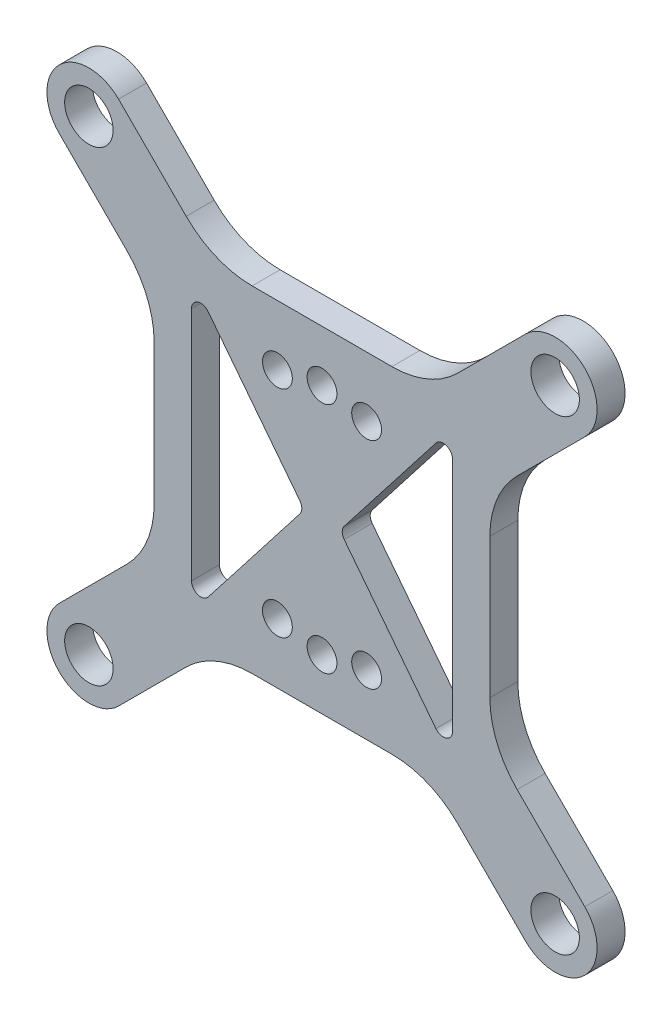
SolidWorks part; units mm, degrees
material "环氧板"
ref_plane "前视基准面" through (0, 0, 0) normal (0, 0, 1) x (1, 0, 0)
ref_plane "上视基准面" through (0, 0, 0) normal (0, 1, 0) x (1, 0, 0)
ref_plane "右视基准面" through (0, 0, 0) normal (1, 0, 0) x (0, 0, -1)
sketch "草图1" plane through (0, 0, 0) normal (0, 0, 1) x (1, 0, 0)
  line L0 (-25, -25) -> (25, 25) construction
  line L1 (-28.182, -21.818) -> (21.818, 28.182)
  line L2 (-21.818, -28.182) -> (28.182, 21.818)
  line L3 (-25, 25) -> (25, -25) construction
  line L4 (-21.818, 28.182) -> (28.182, -21.818)
  line L5 (-28.182, 21.818) -> (21.818, -28.182)
  line L6 (0, 0) -> (122.9733, 0) construction
  line L7 (-25, 25) -> (-25, -25) construction
  line L8 (-25, -25) -> (25, -25) construction
  line L9 (25, -25) -> (25, 25) construction
  line L10 (25, 25) -> (-25, 25) construction
  arc A0 (-28.182, -21.818) -> (-21.818, -28.182) centre (-25, -25) ccw
  arc A1 (28.182, 21.818) -> (21.818, 28.182) centre (25, 25) ccw
  arc A2 (-21.818, 28.182) -> (-28.182, 21.818) centre (-25, 25) ccw
  arc A3 (21.818, -28.182) -> (28.182, -21.818) centre (25, -25) ccw
  circle A4 centre (-25, -25) radius 2.6
  circle A5 centre (25, -25) radius 2.6
  circle A6 centre (25, 25) radius 2.6
  circle A7 centre (-25, 25) radius 2.6
  point P2 (0, 0)
  point P9 (0, 0)
  dimension "D2" = 5.2
  dimension "D1" = 45
  dimension "D3" = 9
  dimension "D4" = 50
extrude "凸台-拉伸1" add sketch "草图1" along normal blind 3 contours L4 A2 L5 L1 A7 | L1 A0 L2 L5 A4 | L5 A3 L4 L2 A5 | L2 A1 L1 L4 A6 | L1 L5 L2 L4
sketch "草图2" plane through (0, 0, 3) normal (0, 0, 1) x (1, 0, 0)
  line L0 (0, 0) -> (30.1676, 0) construction
  line L1 (-18, -18) -> (18, -18)
  line L2 (-18, -18) -> (-18, 18)
  line L3 (-18, 18) -> (18, 18)
  line L4 (18, -18) -> (18, 18)
  line L5 (-18, -18) -> (18, 18) construction
  line L6 (-18, 18) -> (18, -18) construction
  line L7 (0, 0) -> (25, 25) construction
  point P0 (0, 0)
  dimension "D1" = 36
extrude "凸台-拉伸2" add sketch "草图2" against normal blind 3
sketch "草图3" plane through (0, 0, 3) normal (0, 0, 1) x (1, 0, 0)
  line L0 (0, 12.5) -> (0, -12.5) construction
  line L1 (-4.7835, -11.5485) -> (4.7835, 11.5485) construction
  circle A0 centre (0, -12.5) radius 1.6
  circle A1 centre (0, 12.5) radius 1.6
  circle A2 centre (0, 0) radius 12.5 construction
  circle A3 centre (4.7835, 11.5485) radius 1.6
  circle A4 centre (-4.7835, -11.5485) radius 1.6
  circle A5 centre (4.7835, -11.5485) radius 1.6
  circle A6 centre (-4.7835, 11.5485) radius 1.6
  point P4 (0, 0)
  point P9 (0, 0)
  dimension "D1" = 3.2
  dimension "D2" = 25
  dimension "D3" = 22.5
extrude "切除-拉伸1" cut sketch "草图3" against normal up to next
sketch "草图4" plane through (0, 0, 3) normal (0, 0, 1) x (1, 0, 0)
  line L0 (18, -11.636) -> (18, 11.636) construction
  line L1 (14, 18) -> (-14, 18)
  line L2 (14, 18) -> (14, -18)
  line L3 (14, -18) -> (-14, -18)
  line L4 (-14, 18) -> (-14, -18)
  line L5 (14, 18) -> (-14, -18) construction
  line L6 (14, -18) -> (-14, 18) construction
  line L7 (-11.636, -18) -> (11.636, -18) construction
  line L8 (14, -15.5568) -> (-12.0997, 18)
  line L9 (-14, 15.5568) -> (12.0997, -18)
  line L10 (0, 0) -> (0, -24.8736) construction
  line L11 (-14, -15.5568) -> (12.0997, 18)
  line L12 (14, 15.5568) -> (-12.0997, -18)
  point P0 (0, 0)
  dimension "D1" = 4
  dimension "D2" = 0
  dimension "D3" = 3
  dimension "D4" = 1.5
extrude "切除-拉伸2" cut sketch "草图4" against normal blind 3 contours L2 L12 L8 | L4 L11 L9
fillet "圆角1" radius 1 6 edges at (1.9003, 0, 1.5) (-1.9003, 0, 1.5) (-14, 15.5568, 1.5) (-14, -15.5568, 1.5) (14, -15.5568, 1.5) (14, 15.5568, 1.5)
fillet "圆角2" radius 10 8 edges at (11.636, -18, 1.5) (-11.636, -18, 1.5) (-18, -11.636, 1.5) (-18, 11.636, 1.5) (-11.636, 18, 1.5) (11.636, 18, 1.5) (18, 11.636, 1.5) (18, -11.636, 1.5)
